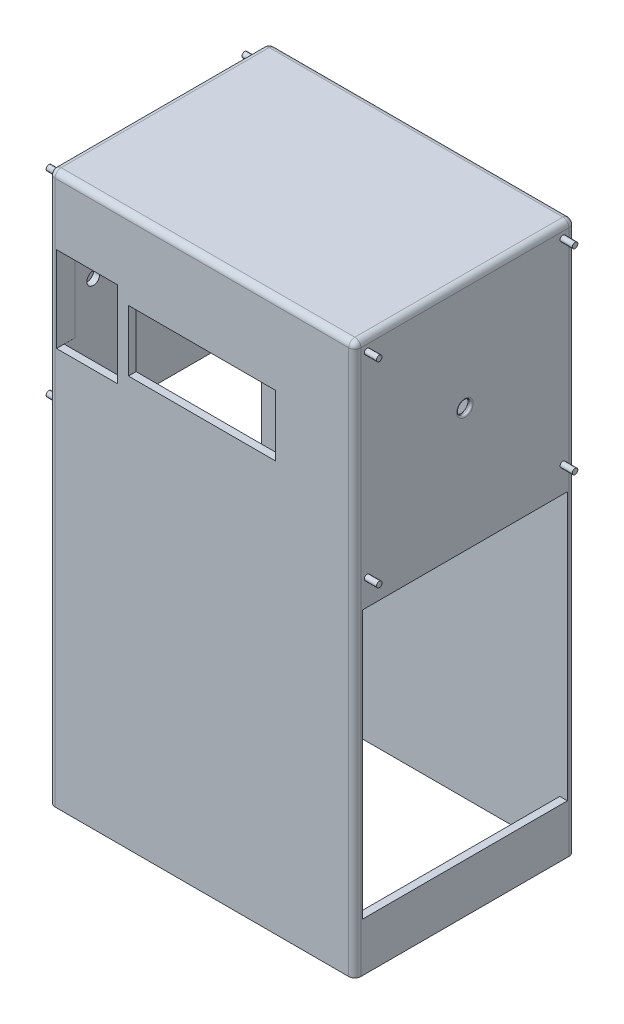
SolidWorks part; units mm, degrees
ref_plane "Front Plane" through (0, 0, 0) normal (0, 0, 1) x (1, 0, 0)
ref_plane "Top Plane" through (0, 0, 0) normal (0, 1, 0) x (1, 0, 0)
ref_plane "Right Plane" through (0, 0, 0) normal (1, 0, 0) x (0, 0, -1)
sketch "Sketch1" plane through (0, 0, 0) normal (0, 1, 0) x (1, 0, 0)
  line L1 (-63.5, -45.72) -> (63.5, -45.72)
  line L2 (-63.5, -45.72) -> (-63.5, 45.72)
  line L3 (-63.5, 45.72) -> (63.5, 45.72)
  line L4 (63.5, -45.72) -> (63.5, 45.72)
  line L5 (-63.5, -45.72) -> (63.5, 45.72) construction
  line L6 (-63.5, 45.72) -> (63.5, -45.72) construction
  point P0 (0, 0)
  dimension "D1" = 91.44
  dimension "D2" = 127
extrude "Boss-Extrude1" add sketch "Sketch1" along normal blind 228.6
sketch "Sketch2" plane through (63.5, 0, 0) normal (1, 0, 0) x (0, 0, -1)
  line L1 (-45.72, 137.16) -> (45.72, 137.16) construction
  line L2 (-45.72, 137.16) -> (-45.72, 228.6) construction
  line L3 (-45.72, 228.6) -> (45.72, 228.6) construction
  line L4 (45.72, 137.16) -> (45.72, 228.6) construction
  line L5 (-45.72, 137.16) -> (45.72, 228.6) construction
  line L6 (-45.72, 228.6) -> (45.72, 137.16) construction
  circle A0 centre (0, 182.88) radius 2.667
  point P0 (0, 182.88)
  dimension "D2" = 5.334
  dimension "D1" = 91.44
sketch "Sketch3" plane through (0, 0, 0) normal (0, -1, 0) x (1, 0, 0)
  line L0 (63.5, 45.72) -> (63.5, -45.72) construction
  line L1 (-60.325, -42.545) -> (60.325, -42.545)
  line L2 (-60.325, -42.545) -> (-60.325, 42.545)
  line L3 (-60.325, 42.545) -> (60.325, 42.545)
  line L4 (60.325, -42.545) -> (60.325, 42.545)
  line L5 (-60.325, -42.545) -> (60.325, 42.545) construction
  line L6 (-60.325, 42.545) -> (60.325, -42.545) construction
  line L7 (-63.5, 45.72) -> (63.5, 45.72) construction
  point P0 (0, 0)
  dimension "D1" = 3.175
  dimension "D2" = 3.175
extrude "Cut-Extrude1" cut sketch "Sketch3" against normal blind 226.06
extrude "Cut-Extrude2" cut sketch "Sketch2" against normal through all contours A0
sketch "Sketch4" plane through (63.5, 0, 0) normal (1, 0, 0) x (0, 0, -1)
  line L3 (-45.72, 228.6) -> (45.72, 228.6) construction
  circle A0 centre (-40.64, 223.52) radius 1.143
  circle A1 centre (40.64, 223.52) radius 1.143
  circle A2 centre (40.64, 142.24) radius 1.143
  circle A3 centre (-40.64, 142.24) radius 1.143
  point P0 (0, 182.88)
  dimension "D7" = 2.286
extrude "Boss-Extrude3" add sketch "Sketch4" along normal blind 5.08
sketch "Sketch5" plane through (60.325, 0, 0) normal (-1, 0, 0) x (0, 0, 1)
  circle A0 centre (0, 182.88) radius 20.32
  dimension "D1" = 40.64
extrude "Cut-Extrude3" cut sketch "Sketch5" against normal blind 1.27
fillet "Fillet1" radius 0.762 1 edges at (61.595, 182.88, 2.667)
fillet "Fillet2" radius 0.762 1 edges at (63.5, 182.88, -2.667)
sketch "Sketch6" plane through (0, 0, 45.72) normal (0, 0, 1) x (1, 0, 0)
  line L0 (0, 0) -> (0, 228.6) construction
  line L1 (-63.5, 228.6) -> (63.5, 228.6) construction
  line L3 (2.7526, 228.6) -> (2.7526, 182.88) construction
  line L4 (-30.48, 170.18) -> (30.48, 170.18)
  line L5 (30.48, 170.18) -> (30.48, 195.58)
  line L6 (-30.48, 170.18) -> (-30.48, 195.58)
  line L7 (30.48, 195.58) -> (-30.48, 195.58)
  line L8 (-30.48, 182.88) -> (30.48, 182.88) construction
  point P10 (0, 170.18)
  dimension "D1" = 45.72
  dimension "D2" = 60.96
  dimension "D3" = 25.4
mirror "Mirror2" about plane through (0, 0, 0) normal (1, 0, 0) of "Cut-Extrude3", "Boss-Extrude3"
fillet "Fillet3" radius 0.762 2 edges at (-61.595, 182.88, -2.667) (-63.5, 182.88, -2.667)
extrude "Cut-Extrude4" cut sketch "Sketch6" against normal through all
fillet "Fillet4" radius 2.54 8 edges at (63.5, 228.6, 0) (0, 228.6, 45.72) (0, 228.6, -45.72) (-63.5, 228.6, 0) (-63.5, 114.3, -45.72) (-63.5, 114.3, 45.72) (63.5, 114.3, 45.72) (63.5, 114.3, -45.72)
sketch "Sketch7" plane through (63.5, 0, 0) normal (1, 0, 0) x (0, 0, -1)
  line L0 (45.72, 226.06) -> (45.72, 0) construction
  line L1 (-42.545, 20.32) -> (42.545, 20.32)
  line L2 (-42.545, 20.32) -> (-42.545, 131.4726)
  line L3 (-42.545, 131.4726) -> (42.545, 131.4726)
  line L4 (42.545, 20.32) -> (42.545, 131.4726)
  line L5 (-42.545, 20.32) -> (42.545, 131.4726) construction
  line L6 (-42.545, 131.4726) -> (42.545, 20.32) construction
  line L7 (-45.72, 0) -> (-45.72, 226.06) construction
  line L8 (-43.18, 0) -> (43.18, 0) construction
  point P0 (0, 75.8963)
  dimension "D1" = 3.175
  dimension "D2" = 3.175
  dimension "D3" = 20.32
extrude "Cut-Extrude5" cut sketch "Sketch7" against normal through all
sketch "Sketch10" plane through (60.325, 0, 0) normal (-1, 0, 0) x (0, 0, 1)
  line L0 (0, 182.88) -> (-30.48, 182.88) construction
  line L1 (-43.18, 226.06) -> (43.18, 226.06) construction
  circle A0 centre (-30.48, 182.88) radius 2.667
  dimension "D2" = 5.334
  dimension "D1" = 30.48
extrude "Cut-Extrude6" cut sketch "Sketch10" against normal blind 2.54
sketch "Sketch11" plane through (60.325, 0, 0) normal (-1, 0, 0) x (0, 0, 1)
  line L0 (-30.48, 182.88) -> (-45.72, 182.88)
  dimension "D1" = 15.24
sketch "Sketch12" plane through (0, 0, -45.72) normal (0, 0, -1) x (-1, 0, 0)
  line L1 (-34.8104, 182.8079) -> (-34.8104, 200.5879)
  line L2 (-34.8104, 182.8079) -> (-34.8104, 165.0279)
  line L3 (-34.8104, 165.0279) -> (-60.2104, 165.0279)
  line L4 (-60.2104, 165.0279) -> (-60.2104, 182.8079)
  line L5 (-34.8104, 200.5879) -> (-60.2104, 200.5879)
  line L6 (-60.2104, 200.5879) -> (-60.2104, 182.8079)
  dimension "D1" = 25.4
  dimension "D2" = 17.78
extrude "Cut-Extrude7" cut sketch "Sketch12" against normal blind 7.62
sketch "Sketch13" plane through (-60.325, 0, 0) normal (1, 0, 0) x (0, 0, -1)
  line L0 (0, 182.88) -> (-30.48, 182.88) construction
  circle A0 centre (-30.48, 182.88) radius 2.667
  dimension "D2" = 5.334
  dimension "D1" = 30.48
extrude "Cut-Extrude8" cut sketch "Sketch13" against normal blind 2.54
sketch "Sketch15" plane through (-60.325, 0, 0) normal (1, 0, 0) x (0, 0, -1)
  line L0 (-30.48, 182.88) -> (-45.72, 182.88)
  dimension "D1" = 15.24
sketch "Sketch16" plane through (0, 0, 45.72) normal (0, 0, 1) x (1, 0, 0)
  line L0 (-60.3464, 182.9342) -> (-60.3464, 200.7142)
  line L1 (-60.3464, 182.9342) -> (-60.3464, 165.1542)
  line L2 (-60.3464, 165.1542) -> (-34.9464, 165.1542)
  line L3 (-34.9464, 165.1542) -> (-34.9464, 200.7142)
  line L4 (-34.9464, 200.7142) -> (-60.3464, 200.7142)
  dimension "D1" = 17.78
  dimension "D2" = 17.78
  dimension "D3" = 25.4
extrude "Cut-Extrude9" cut sketch "Sketch16" against normal blind 7.62
sketch "Sketch17" plane through (-63.5, 0, 0) normal (-1, 0, 0) x (0, 0, 1)
  line L0 (0, 182.88) -> (53.975, 182.88)
  dimension "D1" = 53.975
